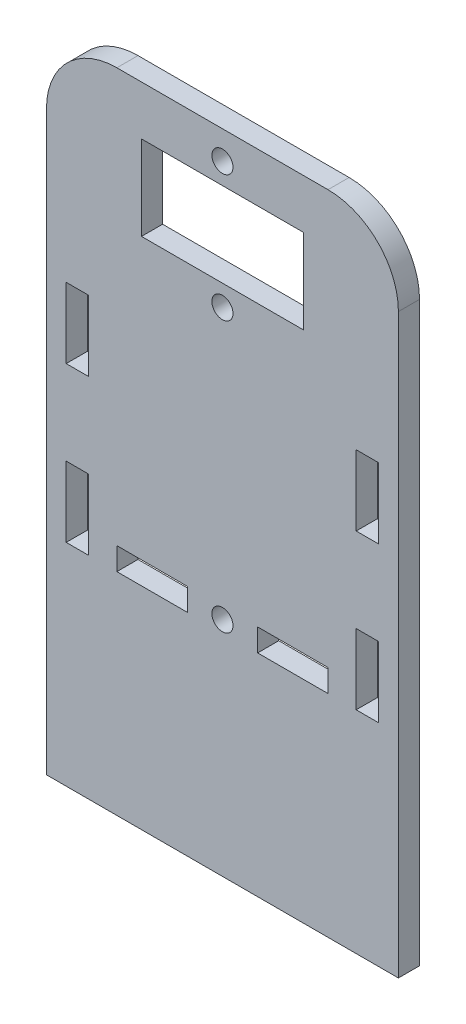
SolidWorks part; units mm, degrees
ref_plane "Alzado" through (0, 0, 0) normal (0, 0, 1) x (1, 0, 0)
ref_plane "Planta" through (0, 0, 0) normal (0, 1, 0) x (1, 0, 0)
ref_plane "Vista lateral" through (0, 0, 0) normal (1, 0, 0) x (0, 0, -1)
sketch "Croquis1" plane through (0, 0, 0) normal (0, 0, 1) x (1, 0, 0)
  line L0 (0, 0) -> (0, 46) construction
  line L1 (25, -46) -> (-25, -46)
  line L2 (25, -46) -> (25, 36)
  line L3 (15, 46) -> (-15, 46)
  line L4 (-25, -46) -> (-25, 36)
  line L5 (25, -46) -> (-25, 46) construction
  line L6 (25, 46) -> (-25, -46) construction
  line L7 (-22.2, 6) -> (-19, 6)
  line L8 (-22.2, 6) -> (-22.2, 16)
  line L9 (-22.2, 16) -> (-19, 16)
  line L10 (-19, 6) -> (-19, 16)
  line L11 (-22.2, 6) -> (-19, 16) construction
  line L12 (-22.2, 16) -> (-19, 6) construction
  line L13 (0, 0) -> (-25, 0) construction
  line L14 (-19, -6) -> (-19, -16)
  line L15 (-22.2, -16) -> (-19, -16)
  line L16 (-22.2, -6) -> (-22.2, -16)
  line L17 (-22.2, -6) -> (-19, -6)
  line L18 (22.2, 16) -> (19, 16)
  line L19 (19, 6) -> (19, 16)
  line L20 (22.2, 6) -> (22.2, 16)
  line L21 (22.2, 6) -> (19, 6)
  line L22 (22.2, -6) -> (19, -6)
  line L23 (22.2, -6) -> (22.2, -16)
  line L24 (22.2, -16) -> (19, -16)
  line L25 (19, -6) -> (19, -16)
  line L26 (0, 33) -> (-25, 33) construction
  line L27 (-11.5, 27) -> (11.5, 27)
  line L28 (-11.5, 27) -> (-11.5, 39)
  line L29 (-11.5, 39) -> (11.5, 39)
  line L30 (11.5, 27) -> (11.5, 39)
  line L31 (-11.5, 27) -> (11.5, 39) construction
  line L32 (-11.5, 39) -> (11.5, 27) construction
  line L33 (15, -12.8) -> (5, -12.8)
  line L34 (-15, -16) -> (-5, -16)
  line L35 (-15, -16) -> (-15, -12.8)
  line L36 (-15, -12.8) -> (-5, -12.8)
  line L37 (-5, -16) -> (-5, -12.8)
  line L38 (-15, -16) -> (-5, -12.8) construction
  line L39 (-15, -12.8) -> (-5, -16) construction
  line L40 (5, -16) -> (5, -12.8)
  line L41 (15, -16) -> (5, -16)
  line L42 (15, -16) -> (15, -12.8)
  line L43 (-5, -14.4) -> (5, -14.4) construction
  arc A0 (25, 36) -> (15, 46) centre (15, 36) ccw
  arc A1 (-15, 46) -> (-25, 36) centre (-15, 36) ccw
  circle A2 centre (0, 42) radius 1.5
  circle A3 centre (0, 24) radius 1.5
  circle A4 centre (0, -14.4) radius 1.5
  point P0 (0, 0)
  point P12 (-20.6, 11)
  point P32 (0, 33)
  point P43 (-10, -14.4)
  point P54 (0, -10.5168)
  point P55 (0, 0)
  point P56 (0, -14.4)
  dimension "D3" = 10
  dimension "D11" = 3
  dimension "D15" = 3
  dimension "D1" = 50
  dimension "D2" = 92
  dimension "D4" = 2.8
  dimension "D5" = 30
  dimension "D6" = 3.2
  dimension "D7" = 10
  dimension "D8" = 12
  dimension "D9" = 23
  dimension "D10" = 7
  dimension "D12" = 4
  dimension "D13" = 10
  dimension "D14" = 10
extrude "Saliente-Extruir1" add sketch "Croquis1" along normal blind 3
